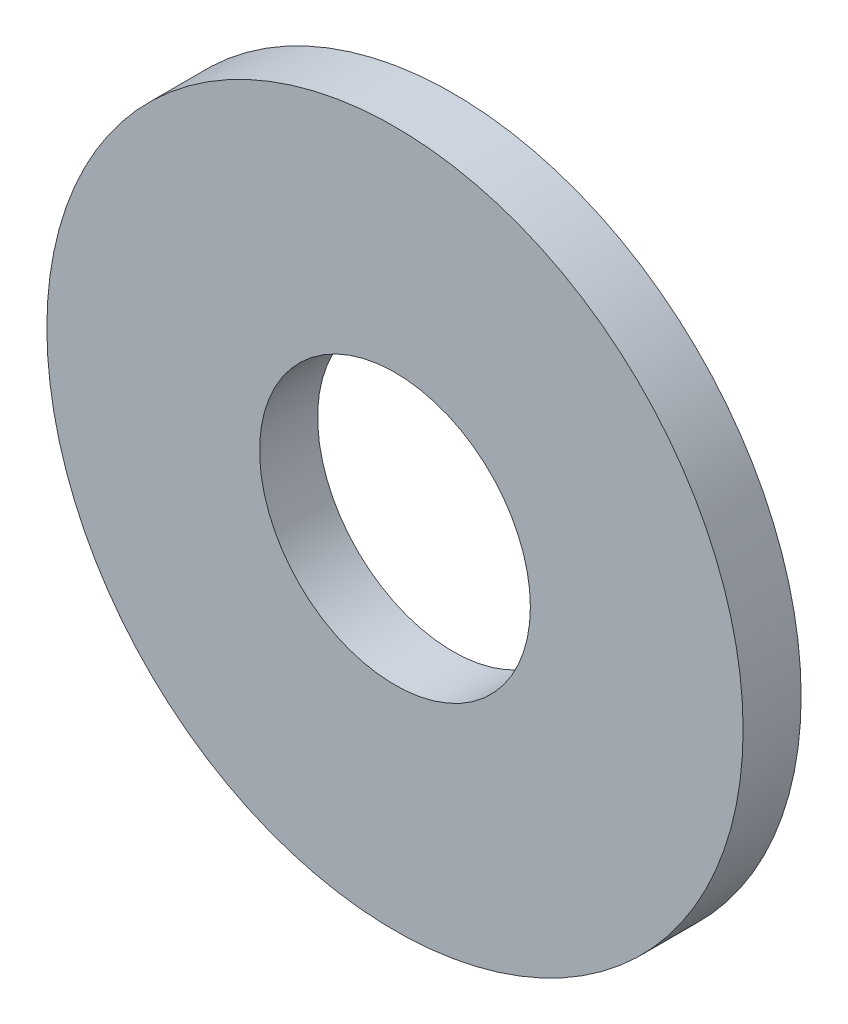
SolidWorks part; units mm, degrees
ref_plane "Спереди" through (0, 0, 0) normal (0, 0, 1) x (1, 0, 0)
ref_plane "Сверху" through (0, 0, 0) normal (0, 1, 0) x (1, 0, 0)
ref_plane "Справа" through (0, 0, 0) normal (1, 0, 0) x (0, 0, -1)
sketch "Эскиз1" plane through (0, 0, 0) normal (0, 0, 1) x (1, 0, 0)
  circle A0 centre (0, 0) radius 9
  circle A1 centre (0, 0) radius 3.5
  dimension "D1" = 18
  dimension "D2" = 7
extrude "Вытянуть1" add sketch "Эскиз1" along normal blind 1.5
